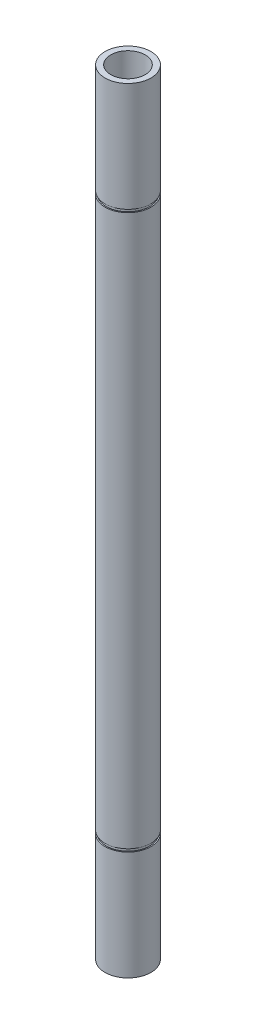
SolidWorks part; units mm, degrees
material "1060 Alloy"
ref_plane "Front Plane" through (0, 0, 0) normal (0, 0, 1) x (1, 0, 0)
ref_plane "Top Plane" through (0, 0, 0) normal (0, 1, 0) x (1, 0, 0)
ref_plane "Right Plane" through (0, 0, 0) normal (1, 0, 0) x (0, 0, -1)
sketch "Sketch1" plane through (0, 0, 0) normal (0, 0, 1) x (1, 0, 0)
  line L0 (0, 64.3023) -> (0, -80.2699) construction
  line L1 (-3, 67.5) -> (-4, 67.5)
  line L2 (-4, 67.5) -> (-4, 48.5)
  line L3 (-4, 48.5) -> (-3.8, 48.5)
  line L4 (-3.8, 48.5) -> (-3.8, 48)
  line L5 (-3.8, 48) -> (-4, 48)
  line L6 (-30.6471, 0) -> (35.9901, 0) construction
  line L7 (-4, 48) -> (-4, -48)
  line L8 (-3.8, -48) -> (-4, -48)
  line L9 (-3.8, -48.5) -> (-3.8, -48)
  line L10 (-4, -48.5) -> (-3.8, -48.5)
  line L11 (-4, -67.5) -> (-4, -48.5)
  line L12 (-3, -67.5) -> (-4, -67.5)
  line L13 (-3, 67.5) -> (-3, -67.5)
  point P11 (-4, 58)
  point P14 (-4, 0)
  dimension "D1" = 135
  dimension "D2" = 8
  dimension "D3" = 0.5
  dimension "D4" = 0.2
  dimension "D5" = 19
  dimension "D6" = 1
revolve "Revolve2" add sketch "Sketch1" angle 360 about L0
